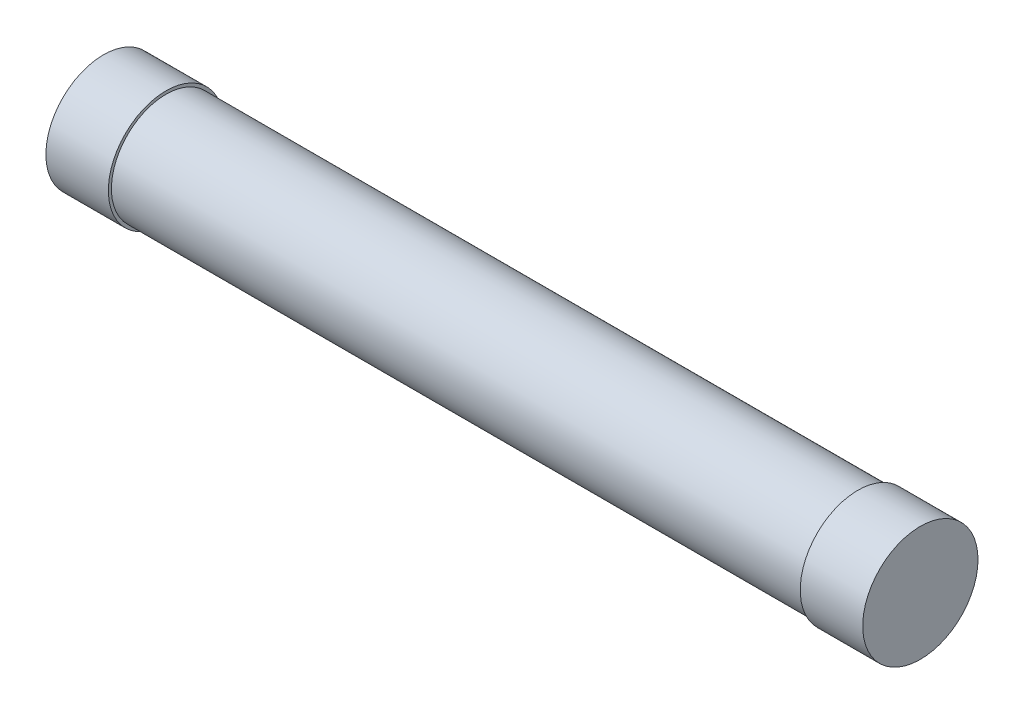
SolidWorks part; units mm, degrees
ref_plane "Front Plane" through (0, 0, 0) normal (0, 0, 1) x (1, 0, 0)
ref_plane "Top Plane" through (0, 0, 0) normal (0, 1, 0) x (1, 0, 0)
ref_plane "Right Plane" through (0, 0, 0) normal (1, 0, 0) x (0, 0, -1)
sketch "Sketch1" plane through (0, 0, 0) normal (1, 0, 0) x (0, 0, -1)
  circle A0 centre (0, 0) radius 9.525
  dimension "D1" = 19.05
extrude "Boss-Extrude1" add sketch "Sketch1" along normal mid plane 134.9375
sketch "Sketch2" plane through (0, 0, 0) normal (1, 0, 0) x (0, 0, -1)
  circle A0 centre (0, 0) radius 9.025
  circle A1 centre (0, 0) radius 9.525
  dimension "D1" = 18.05
extrude "Cut-Extrude1" cut sketch "Sketch2" against normal mid plane 114.3
